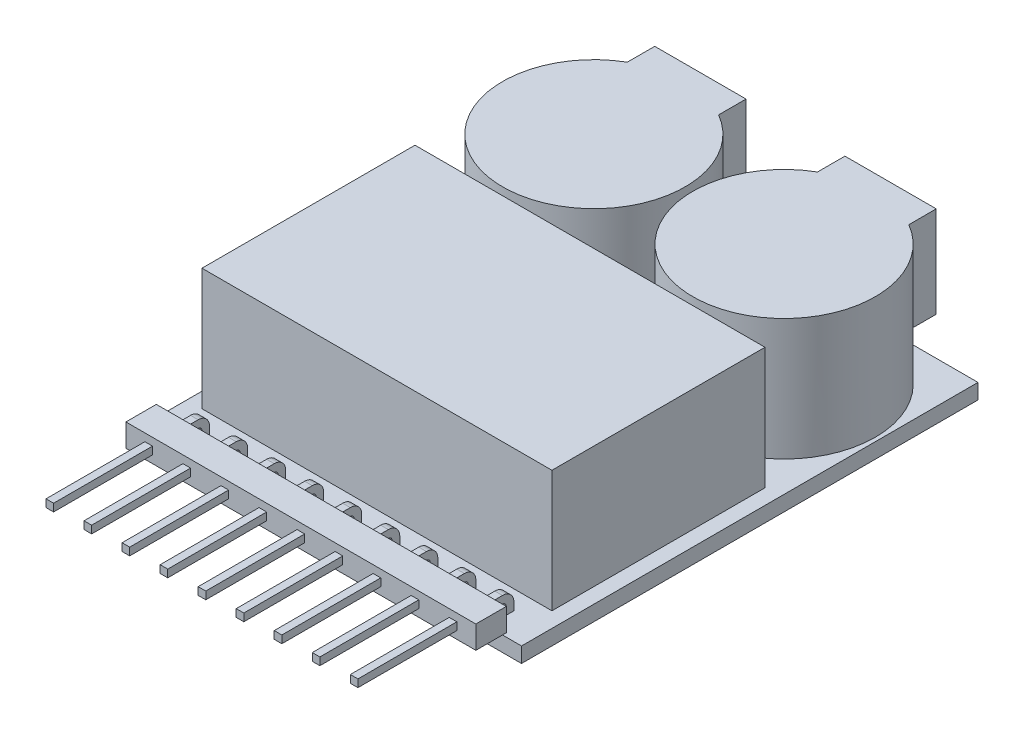
SolidWorks part; units mm, degrees
material "PPS"
ref_plane "Ebene vorne" through (0, 0, 0) normal (0, 0, 1) x (1, 0, 0)
ref_plane "Ebene oben" through (0, 0, 0) normal (0, 1, 0) x (1, 0, 0)
ref_plane "Ebene rechts" through (0, 0, 0) normal (1, 0, 0) x (0, 0, -1)
sketch "Skizze1" plane through (0, 0, 0) normal (0, 1, 0) x (1, 0, 0)
  line L1 (-12.5, -15) -> (12.5, -15)
  line L2 (-12.5, -15) -> (-12.5, 15)
  line L3 (-12.5, 15) -> (12.5, 15)
  line L4 (12.5, -15) -> (12.5, 15)
  line L5 (-12.5, -15) -> (12.5, 15) construction
  line L6 (-12.5, 15) -> (12.5, -15) construction
  point P0 (0, 0)
  dimension "D1" = 30
  dimension "D2" = 25
extrude "Grundplatte" add sketch "Skizze1" along normal blind 1
sketch "Skizze2" plane through (0, 1, 0) normal (0, 1, 0) x (1, 0, 0)
  line L0 (-12.5, -15) -> (12.5, -15) construction
  line L1 (-11.5, -12) -> (11.5, -12)
  line L2 (-11.5, -12) -> (-11.5, 2)
  line L3 (-11.5, 2) -> (11.5, 2)
  line L4 (11.5, -12) -> (11.5, 2)
  line L5 (-11.5, -12) -> (11.5, 2) construction
  line L6 (-11.5, 2) -> (11.5, -12) construction
  point P0 (0, -5)
  dimension "D1" = 14
  dimension "D2" = 23
  dimension "D3" = 3
extrude "Ziffernblatt" add sketch "Skizze2" along normal blind 8
sketch "Skizze3" plane through (0, 1, 0) normal (0, 1, 0) x (1, 0, 0)
  line L0 (0, 12.3887) -> (0, -8.8432) construction
  circle A0 centre (-6.25, 8.5057) radius 6
  circle A1 centre (6.25, 8.5057) radius 6
  dimension "D1" = 12
  dimension "D2" = 12.5
extrude "Buzzer1" add sketch "Skizze3" along normal blind 8
ref_plane "Hilfsebene_Buzzer" through (0, 0, -14.5057) normal (0, 0, -1) x (-1, 0, 0)
sketch "Skizze4" plane through (0, 0, -14.5057) normal (0, 0, -1) x (-1, 0, 0)
  line L1 (-0.25, 9) -> (-12.25, 9) construction
  line L2 (-9.25, 3) -> (-3.25, 3)
  line L3 (-9.25, 3) -> (-9.25, 9)
  line L4 (-9.25, 9) -> (-3.25, 9)
  line L5 (0, -3.856) -> (0, 17.444) construction
  line L6 (-3.25, 3) -> (-3.25, 9)
  line L7 (-9.25, 3) -> (-3.25, 9) construction
  line L8 (-9.25, 9) -> (-3.25, 3) construction
  line L9 (-0.25, 9) -> (-12.25, 9) construction
  line L10 (9.25, 9) -> (3.25, 3) construction
  line L11 (9.25, 3) -> (3.25, 9) construction
  line L12 (3.25, 3) -> (3.25, 9)
  line L13 (9.25, 9) -> (3.25, 9)
  line L14 (9.25, 3) -> (9.25, 9)
  line L15 (9.25, 3) -> (3.25, 3)
  point P0 (-6.25, 6)
  point P11 (-6.25, 9)
  point P16 (6.25, 6)
  dimension "D1" = 6
  dimension "D2" = 6
extrude "Buzzer2" add sketch "Skizze4" along direction (0, 0, -1) on the side of the normal blind 1 and the other way blind 5
ref_plane "Hilfsebene_Kontaktstifte" through (10, 0, 0) normal (1, 0, 0) x (0, 0, -1)
sketch "Skizze5" plane through (10, 0, 0) normal (1, 0, 0) x (0, 0, -1)
  line L0 (-13.5, 1) -> (-13.5, 1.5) construction
  line L1 (-15, 1) -> (15, 1) construction
  line L2 (-14, 2) -> (-23.5, 2) construction
  line L3 (-15, 1) -> (-15, 0) construction
  line L4 (-13.25, 1) -> (-13.25, 1.5)
  line L5 (-14, 2.25) -> (-23.5, 2.25)
  line L6 (-13.75, 1) -> (-13.75, 1.5)
  line L7 (-14, 1.75) -> (-23.5, 1.75)
  line L8 (-23.5, 2.25) -> (-23.5, 1.75)
  line L9 (-13.75, 1) -> (-13.25, 1)
  arc A0 (-13.5, 1.5) -> (-14, 2) centre (-14, 1.5) ccw construction
  arc A1 (-13.25, 1.5) -> (-14, 2.25) centre (-14, 1.5) ccw
  arc A2 (-13.75, 1.5) -> (-14, 1.75) centre (-14, 1.5) ccw
  point P9 (-13.5, 2)
  dimension "D4" = 0.5
  dimension "D1" = 1
  dimension "D2" = 10
  dimension "D3" = 1.5
  dimension "D5" = 0.25
  dimension "D6" = 0.25
extrude "Kontaktstift" add sketch "Skizze5" along normal mid plane 0.5
pattern_linear "Muster_Kontaktstift" count 9 spacing 2.5 along (-1, 0, 0) of "Kontaktstift"
sketch "Skizze6" plane through (0, 0, 15) normal (0, 0, 1) x (1, 0, 0)
  line L0 (0, -0.7371) -> (0, 5.889) construction
  line L1 (-11.5, 2.75) -> (11.5, 2.75)
  line L2 (-11.5, 2.75) -> (-11.5, 1.25)
  line L3 (-11.5, 1.25) -> (11.5, 1.25)
  line L4 (11.5, 2.75) -> (11.5, 1.25)
  line L5 (-11.5, 2.75) -> (11.5, 1.25) construction
  line L6 (-11.5, 1.25) -> (11.5, 2.75) construction
  line L7 (-0.25, 2) -> (0.4353, 2) construction
  line L9 (0.25, 2.25) -> (0.25, 1.75) construction
  line L10 (12.5, 1) -> (12.5, 0) construction
  point P0 (0, 2)
  point P14 (0.25, 2)
  dimension "D1" = 1.5
  dimension "D2" = 1
extrude "Buchsenanschlag" add sketch "Skizze6" along normal blind 2
